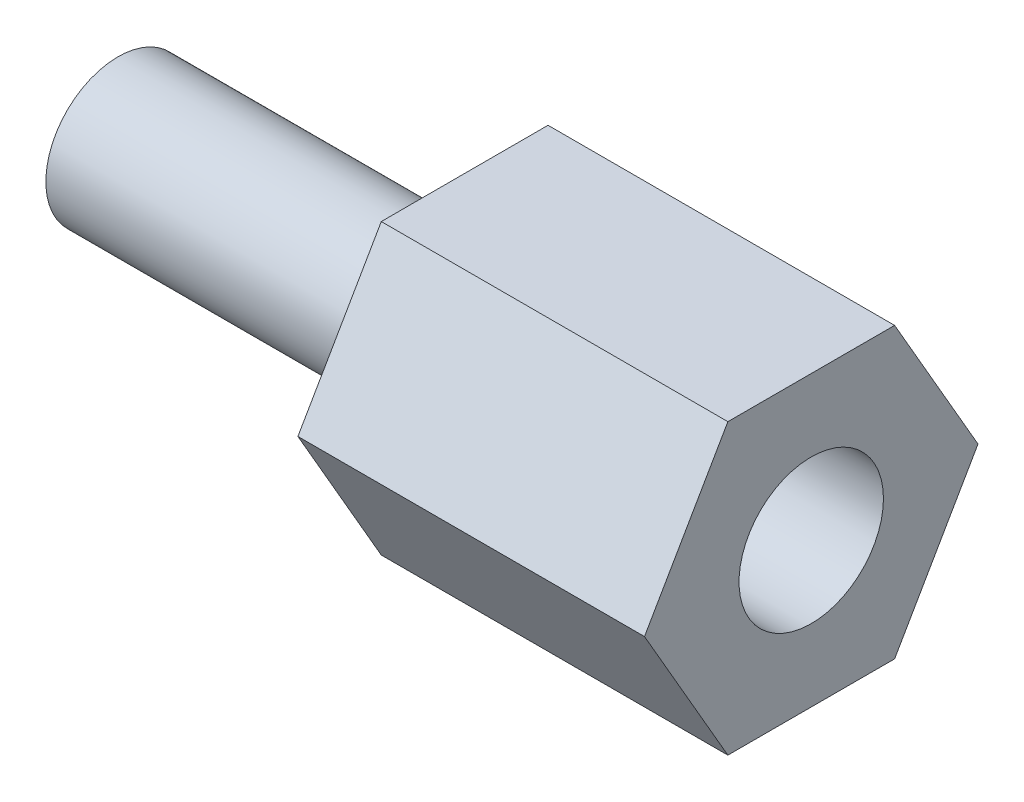
SolidWorks part; units mm, degrees
ref_plane "Front Plane" through (0, 0, 0) normal (0, 0, 1) x (1, 0, 0)
ref_plane "Top Plane" through (0, 0, 0) normal (0, 1, 0) x (1, 0, 0)
ref_plane "Right Plane" through (0, 0, 0) normal (1, 0, 0) x (0, 0, -1)
other "Configuration Table"
sketch "Sketch1" plane through (0, 0, 0) normal (1, 0, 0) x (0, 0, -1)
  circle A0 centre (0, 0) radius 1.25
extrude "Boss-Extrude1" add sketch "Sketch1" against normal blind 6 contours A0
sketch "Sketch2" plane through (0, 0, 0) normal (1, 0, 0) x (0, 0, -1)
  line L1 (2.8868, 0) -> (1.4434, 2.5)
  line L2 (1.4434, 2.5) -> (-1.4434, 2.5)
  line L3 (-1.4434, 2.5) -> (-2.8868, 0)
  line L4 (-2.8868, 0) -> (-1.4434, -2.5)
  line L5 (-1.4434, -2.5) -> (1.4434, -2.5)
  line L6 (1.4434, -2.5) -> (2.8868, 0)
  circle A0 centre (0, 0) radius 2.5 construction
  circle A1 centre (0, 0) radius 1.25
  dimension "D1" = 5
extrude "Boss-Extrude2" add sketch "Sketch2" along normal blind 6 separate body
